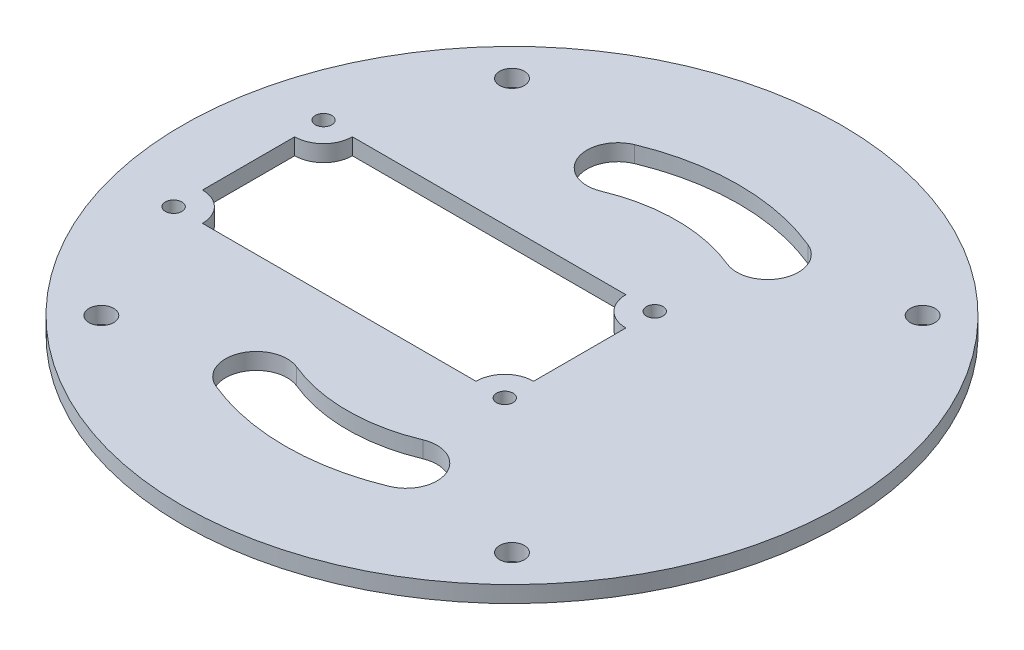
SolidWorks part; units mm, degrees
ref_plane "Alzado" through (0, 0, 0) normal (0, 0, 1) x (1, 0, 0)
ref_plane "Planta" through (0, 0, 0) normal (0, 1, 0) x (1, 0, 0)
ref_plane "Vista lateral" through (0, 0, 0) normal (1, 0, 0) x (0, 0, -1)
sketch "Croquis2" plane through (0, 0, 0) normal (0, 1, 0) x (1, 0, 0)
  line L0 (-40.0059, 0) -> (40.0059, 0) construction
  line L1 (0, 40.0059) -> (0, -40.0059) construction
  line L2 (-28.4766, -9.1) -> (4.7234, -9.1)
  line L3 (0, 0) -> (-10.5238, -25.4067) construction
  line L4 (-31.9766, 5.6) -> (-31.9766, -5.6)
  line L5 (-28.4766, 9.1) -> (4.7234, 9.1)
  line L6 (0, 0) -> (10.5238, -25.4067) construction
  line L7 (8.2234, 5.6) -> (8.2234, -5.6)
  line L8 (0, 0) -> (-24.9255, 24.9255) construction
  line L9 (0, 0) -> (-10.5238, 25.4067) construction
  line L10 (0, 0) -> (10.5238, 25.4067) construction
  circle A0 centre (0, 0) radius 40.0059
  circle A1 centre (0, 0) radius 40.0059
  circle A2 centre (-31.9766, 9.1) radius 0.9954
  circle A3 centre (-31.9766, -9.1) radius 1.0041
  circle A4 centre (8.2234, 9.1) radius 1.0062
  circle A5 centre (8.2234, -9.1) radius 1.0046
  arc A6 (-31.9766, 5.6) -> (-28.4766, 9.1) centre (-31.9766, 9.1) ccw
  arc A7 (-31.9766, -5.6) -> (-28.4766, -9.1) centre (-31.9766, -9.1) cw
  arc A8 (4.7234, -9.1) -> (8.2234, -5.6) centre (8.2234, -9.1) cw
  arc A9 (8.2234, 5.6) -> (4.7234, 9.1) centre (8.2234, 9.1) cw
  arc A10 (-7.6537, -18.4776) -> (7.6537, -18.4776) centre (0, 0) ccw
  arc A11 (-10.5238, -25.4067) -> (10.5238, -25.4067) centre (0, 0) ccw
  circle A12 centre (0, 0) radius 23.75 construction
  arc A13 (-10.5238, 25.4067) -> (-7.6537, 18.4776) centre (-9.0887, 21.9421) ccw
  arc A14 (7.6537, 18.4776) -> (10.5238, 25.4067) centre (9.0887, 21.9421) ccw
  arc A15 (-7.6537, -18.4776) -> (-10.5238, -25.4067) centre (-9.0887, -21.9421) ccw
  arc A16 (10.5238, -25.4067) -> (7.6537, -18.4776) centre (9.0887, -21.9421) ccw
  arc A17 (7.6537, 18.4776) -> (-7.6537, 18.4776) centre (0, 0) ccw
  arc A18 (10.5238, 25.4067) -> (-10.5238, 25.4067) centre (0, 0) ccw
  circle A23 centre (0, 0) radius 35.25 construction
  circle A24 centre (-24.9255, 24.9255) radius 1.5
  circle A25 centre (24.9255, 24.9255) radius 1.5
  circle A26 centre (24.9255, -24.9255) radius 1.5
  circle A27 centre (-24.9255, -24.9255) radius 1.5
  dimension "D7" = 45
  dimension "D8" = 4
  dimension "D1" = 22.5
  dimension "D2" = 22.5
  dimension "D3" = 45
  dimension "D4" = 22.5
  dimension "D5" = 22.5
  dimension "D6" = 45
extrude "Saliente-Extruir1" add sketch "Croquis2" along normal blind 2 separate body
